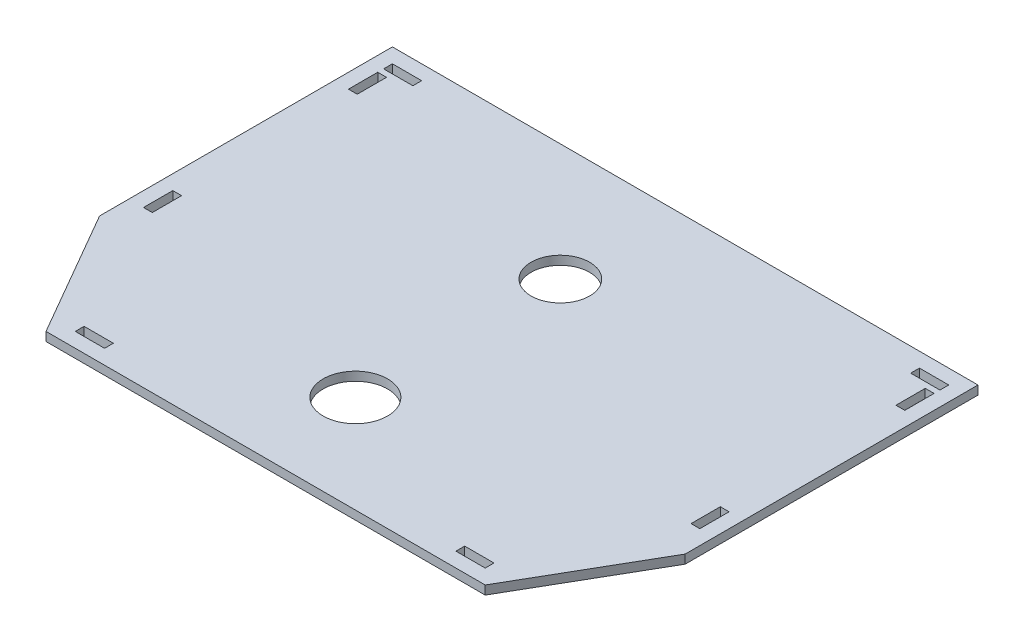
SolidWorks part; units mm, degrees
ref_plane "Plano frontal" through (0, 0, 0) normal (0, 0, 1) x (1, 0, 0)
ref_plane "Plano superior" through (0, 0, 0) normal (0, 1, 0) x (1, 0, 0)
ref_plane "Plano direito" through (0, 0, 0) normal (1, 0, 0) x (0, 0, -1)
sketch "Esboço1" plane through (0, 0, 0) normal (0, 1, 0) x (1, 0, 0)
  line L2 (0, 0) -> (0, 70)
  line L3 (0, 0) -> (0, -70)
  line L6 (-97.3576, -26.6987) -> (-97.3576, 73.3013)
  line L7 (102.6424, -26.6987) -> (102.6424, 73.3013)
  line L10 (-97.3576, 73.3013) -> (102.6424, 73.3013)
  line L11 (-97.3576, -26.6987) -> (-72.3576, -70)
  line L12 (102.6424, -26.6987) -> (77.6424, -70)
  line L13 (77.6424, -70) -> (-72.3576, -70)
  dimension "D2" = 100
  dimension "D3" = 70
  dimension "D5" = 200
  dimension "D6" = 50
  dimension "D8" = 150
extrude "Ressalto-extrusão1" add sketch "Esboço1" along normal blind 3
sketch "Esboço3" plane through (0, 3, 0) normal (0, 1, 0) x (1, 0, 0)
  line L0 (2.6424, -70) -> (2.6424, -52.3382)
  line L1 (77.6424, -70) -> (-72.3576, -70) construction
  line L2 (102.6424, -26.6987) -> (102.6424, 73.3013) construction
  line L3 (-92.3576, 68.3013) -> (-82.3576, 68.3013)
  line L4 (-92.3576, 68.3013) -> (-92.3576, 65.3013)
  line L5 (-92.3576, 65.3013) -> (-82.3576, 65.3013)
  line L6 (-82.3576, 68.3013) -> (-82.3576, 65.3013)
  line L7 (87.6424, 68.3013) -> (97.6424, 68.3013)
  line L8 (87.6424, 68.3013) -> (87.6424, 65.3013)
  line L9 (87.6424, 65.3013) -> (97.6424, 65.3013)
  line L10 (97.6424, 68.3013) -> (97.6424, 65.3013)
  line L11 (94.625, 63.3013) -> (97.6424, 63.3013)
  line L12 (94.625, 63.3013) -> (94.625, 53.3013)
  line L13 (94.625, 53.3013) -> (97.6424, 53.3013)
  line L14 (97.6424, 63.3013) -> (97.6424, 53.3013)
  line L19 (-97.3576, 73.3013) -> (102.6424, 73.3013) construction
  line L20 (-92.3576, 63.3013) -> (-89.3576, 63.3013)
  line L21 (-92.3576, 63.3013) -> (-92.3576, 53.3013)
  line L22 (-92.3576, 53.3013) -> (-89.3576, 53.3013)
  line L23 (-89.3576, 63.3013) -> (-89.3576, 53.3013)
  line L24 (-92.3576, -6.6987) -> (-89.3576, -6.6987)
  line L25 (-92.3576, -6.6987) -> (-92.3576, -16.6987)
  line L26 (-92.3576, -16.6987) -> (-89.3576, -16.6987)
  line L27 (-89.3576, -6.6987) -> (-89.3576, -16.6987)
  line L28 (-97.3576, -26.6987) -> (-97.3576, 73.3013) construction
  line L30 (94.6424, -6.6987) -> (97.6424, -6.6987)
  line L31 (94.6424, -6.6987) -> (94.6424, -16.6987)
  line L32 (94.6424, -16.6987) -> (97.6424, -16.6987)
  line L33 (97.6424, -6.6987) -> (97.6424, -16.6987)
  line L34 (-67.3576, -65) -> (-57.3576, -65)
  line L35 (-67.3576, -65) -> (-67.3576, -62)
  line L36 (-67.3576, -62) -> (-57.3576, -62)
  line L37 (-57.3576, -65) -> (-57.3576, -62)
  line L38 (72.6424, -65) -> (62.6424, -65)
  line L39 (72.6424, -65) -> (72.6424, -62)
  line L40 (72.6424, -62) -> (62.6424, -62)
  line L41 (62.6424, -65) -> (62.6424, -62)
  dimension "D1" = 5
  dimension "D2" = 5
  dimension "D3" = 3
  dimension "D4" = 3
  dimension "D5" = 5
  dimension "D6" = 10
  dimension "D7" = 5
  dimension "D8" = 10
  dimension "D9" = 10
  dimension "D10" = 10
  dimension "D11" = 5
  dimension "D12" = 10
  dimension "D13" = 10
  dimension "D14" = 3
  dimension "D15" = 5
  dimension "D16" = 5
  dimension "D17" = 3
  dimension "D18" = 10
  dimension "D19" = 10
  dimension "D20" = 5
  dimension "D21" = 3
  dimension "D22" = 10
  dimension "D23" = 10
  dimension "D24" = 5
  dimension "D25" = 5
  dimension "D26" = 3
  dimension "D27" = 10
  dimension "D28" = 3
  dimension "D29" = 10
  dimension "D30" = 5
  dimension "D31" = 5
extrude "Corte-extrusão1" cut sketch "Esboço3" against normal blind 3 contours L34 L37 L36 L35 | L41 L38 L39 L40 | L33 L30 L31 L32 | L14 L11 L12 L13 | L10 L7 L8 L9 | L27 L24 L25 L26 | L23 L20 L21 L22 | L6 L3 L4 L5
sketch "Esboço5" plane through (0, 3, 0) normal (0, 1, 0) x (1, 0, 0)
  line L0 (-97.3576, 73.3013) -> (102.6424, 73.3013) construction
  circle A0 centre (0, 33.3013) radius 10
  circle A1 centre (0, -36.6987) radius 11
  dimension "D1" = 20
  dimension "D2" = 40
  dimension "D3" = 22
  dimension "D4" = 70
extrude "Corte-extrusão2" cut sketch "Esboço5" against normal blind 10
sketch "Esboço6" plane through (0, 3, 0) normal (0, 1, 0) x (1, 0, 0)
  line L0 (0, -25.6987) -> (0, -36.6987)
  line L1 (0, 43.3013) -> (0, 33.3013)
  circle A0 centre (0, -36.6987) radius 11 construction
  circle A1 centre (0, 33.3013) radius 10 construction
